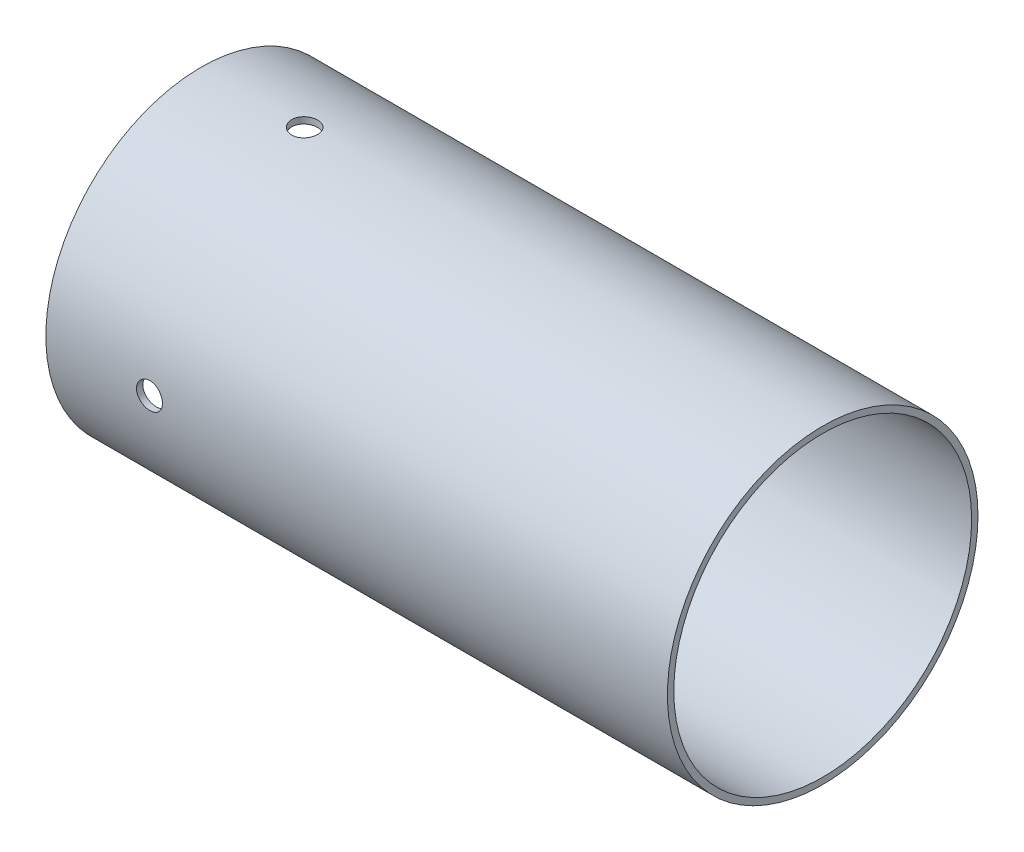
SolidWorks part; units mm, degrees
ref_plane "Front Plane" through (0, 0, 0) normal (1, 0, 0) x (0, 1, 0)
ref_plane "Top Plane" through (0, 0, 0) normal (0, 0, 1) x (0, 1, 0)
ref_plane "Right Plane" through (0, 0, 0) normal (0, 1, 0) x (-1, 0, 0)
sketch "Sketch1" plane through (0, 0, 0) normal (1, 0, 0) x (0, 1, 0)
  circle A0 centre (0, 0) radius 38.0746
  circle A1 centre (0, 0) radius 36.5125
  dimension "D1" = 76.1492
  dimension "D2" = 73.025
extrude "Boss-Extrude1" add sketch "Sketch1" along normal blind 152.4
sketch "Sketch3" plane through (0, 0, 0) normal (0, 1, 0) x (-1, 0, 0)
  line L0 (0, -38.0746) -> (0, 38.0746) construction
  line L1 (0, -38.0746) -> (0, 38.0746) construction
  line L2 (0, 0) -> (-25.4, 0) construction
  circle A0 centre (-25.4, 0) radius 3.175
  dimension "D2" = 6.35
  dimension "D1" = 25.4
extrude "Cut-Extrude1" cut sketch "Sketch3" along normal through all
pattern_circular "CirPattern1" count 4 over 360 about axis through (152.4, 0, 0) along (-1, 0, 0) of "Cut-Extrude1"
